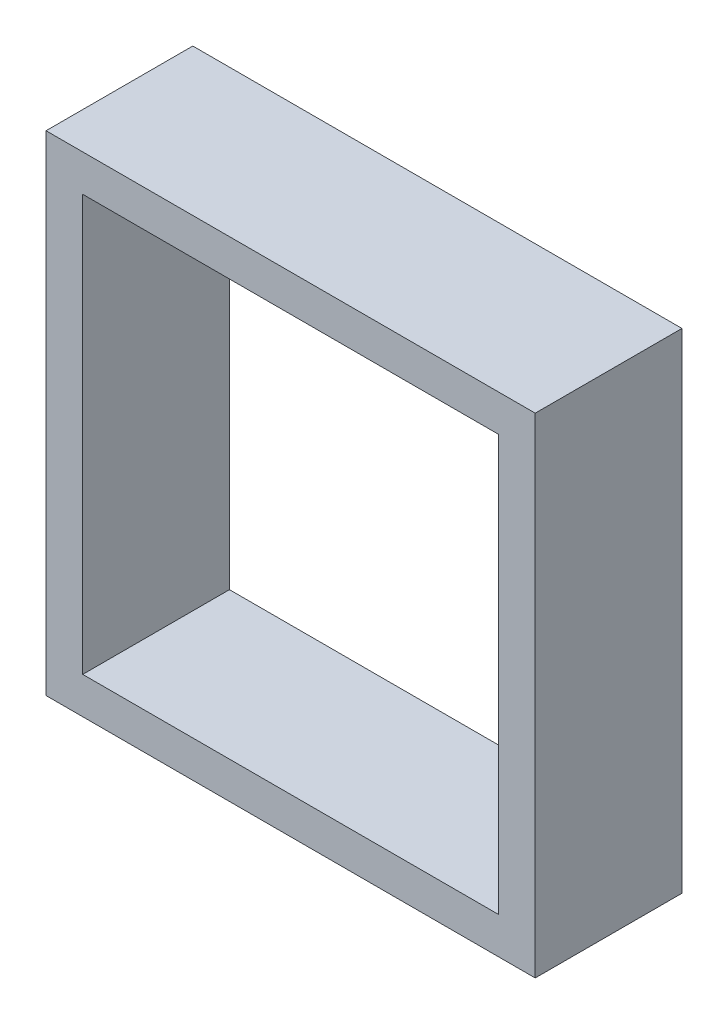
SolidWorks part; units mm, degrees
ref_plane "Front Plane" through (0, 0, 0) normal (0, 0, 1) x (1, 0, 0)
ref_plane "Top Plane" through (0, 0, 0) normal (0, 1, 0) x (1, 0, 0)
ref_plane "Right Plane" through (0, 0, 0) normal (1, 0, 0) x (0, 0, -1)
sketch "Sketch1" plane through (0, 0, 0) normal (0, 0, 1) x (1, 0, 0)
  line L0 (38.1, 38.1) -> (38.1, 469.9)
  line L1 (0, 0) -> (508, 0)
  line L2 (0, 0) -> (0, 508)
  line L3 (0, 508) -> (508, 508)
  line L4 (508, 0) -> (508, 508)
  line L5 (38.1, 469.9) -> (469.9, 469.9)
  line L6 (469.9, 38.1) -> (469.9, 469.9)
  line L7 (38.1, 38.1) -> (469.9, 38.1)
  dimension "D1" = 508
  dimension "D2" = 508
  dimension "D3" = 38.1
extrude "Boss-Extrude1" add sketch "Sketch1" along normal blind 152.4
